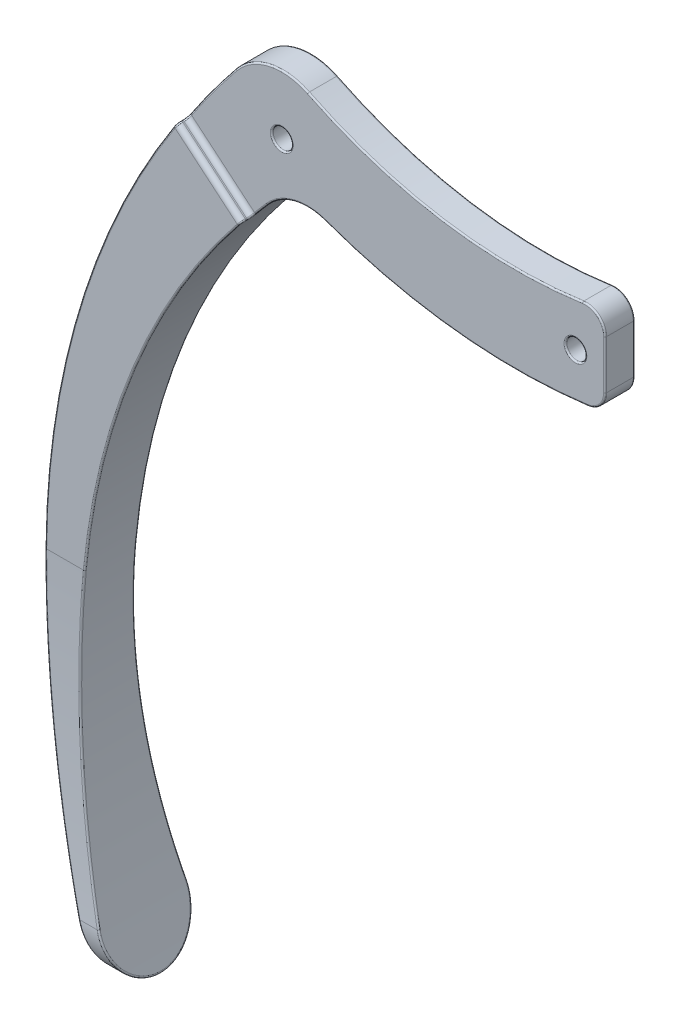
SolidWorks part; units mm, degrees
ref_plane "Front Plane" through (0, 0, 0) normal (0, 0, 1) x (1, 0, 0)
ref_plane "Top Plane" through (0, 0, 0) normal (0, 1, 0) x (1, 0, 0)
ref_plane "Right Plane" through (0, 0, 0) normal (1, 0, 0) x (0, 0, -1)
sketch "Sketch1" plane through (0, 0, 0) normal (0, 0, 1) x (1, 0, 0)
  line L0 (0, 4.5) -> (0, -4.5)
  line L1 (-46.08, -77.96) -> (-47.88, -77.96)
  arc A0 (0, 4.5) -> (-30, 8.5409) centre (-9.0055, 51.0244) cw
  arc A1 (0, -4.5) -> (-28.25, -1.8311) centre (-9.0055, 51.0244) cw
  arc A2 (-28.25, -1.8311) -> (-34.1009, -3.3287) centre (-30.0804, -6.8583) ccw
  arc A3 (-34.1009, -3.3287) -> (-46.08, -77.96) centre (19.2554, -50.17) ccw
  arc A4 (-30, 8.5409) -> (-37.3077, 6.9543) centre (-32.6582, 3.1619) ccw
  arc A5 (-37.3077, 6.9543) -> (-47.88, -77.96) centre (25.0724, -43.9277) ccw
  circle A6 centre (-32.6582, 3.1619) radius 1
  arc A7 (0, 0) -> (-28.6843, 3.0939) centre (-9.0055, 51.0244) cw construction
  circle A8 centre (-3, -0.4394) radius 1
  point P3 (0, 0)
  dimension "D2" = 47.388
  dimension "D3" = 56.25
  dimension "D4" = 28.25
  dimension "D6" = 5.35
  dimension "D7" = 71
  dimension "D9" = 6
  dimension "D10" = 80.5
  dimension "D13" = 2
  dimension "D1" = 9
  dimension "D5" = 30
  dimension "D8" = 77.96
  dimension "D11" = 47.88
  dimension "D12" = 1.8
  dimension "D14" = 3
sketch "Sketch2" plane through (0, 0, 0) normal (0, 0, 1) x (1, 0, 0)
  line L0 (0, -4.5) -> (0, -35) construction
  line L1 (-35.6168, -5.114) -> (-42.1466, 0.3652)
  line L2 (0, -4.5) -> (0, 4.5)
  line L3 (-47.88, -77.96) -> (-46.08, -77.96)
  line L5 (-47.88, -77.96) -> (-46.08, -77.96)
  line L6 (-35.6168, -5.114) -> (0, -35) construction
  arc A6 (-28.25, -1.8311) -> (0, -4.5) centre (-9.0055, 51.0244) ccw
  arc A7 (-28.25, -1.8311) -> (-34.1009, -3.3287) centre (-30.0804, -6.8583) ccw
  arc A8 (-34.1009, -3.3287) -> (-46.08, -77.96) centre (19.2554, -50.17) ccw
  arc A9 (-37.3077, 6.9543) -> (-47.88, -77.96) centre (25.0724, -43.9277) ccw
  arc A10 (-30, 8.5409) -> (-37.3077, 6.9543) centre (-32.6582, 3.1619) ccw
  arc A11 (-30, 8.5409) -> (0, 4.5) centre (-9.0055, 51.0244) ccw
  arc A14 (-35.6168, -5.114) -> (-46.08, -77.96) centre (19.2554, -50.17) ccw
  arc A15 (-42.1466, 0.3652) -> (-47.88, -77.96) centre (25.0724, -43.9277) ccw
  dimension "D5" = 50
  dimension "D1" = 0
extrude "Boss-Extrude1" add sketch "Sketch2" along normal mid plane 10
sketch "Sketch3" plane through (0, 0, 0) normal (1, 0, 0) x (0, 0, -1)
  line L0 (-2.625, -43.4348) -> (-2.625, 5.0652)
  line L1 (-2.625, 5.0652) -> (2.625, 5.0652) construction
  line L2 (2.625, 5.0652) -> (2.625, -43.4348)
  line L3 (-5, 0.3652) -> (5, 0.3652) construction
  line L4 (-2.625, 5.0652) -> (-26.7308, 5.0652)
  line L5 (-26.7308, 5.0652) -> (-26.7308, -87.6392)
  line L6 (-26.7308, -87.6392) -> (29.1462, -87.6392)
  line L7 (29.1462, -87.6392) -> (29.1462, 5.0652)
  line L8 (29.1462, 5.0652) -> (2.625, 5.0652)
  arc A0 (2.625, -43.4348) -> (4.4638, -72.3651) centre (231.1292, -43.4348) ccw
  arc A1 (4.4638, -72.3651) -> (-4.4638, -72.3651) centre (0, -72.9348) cw
  arc A2 (-4.4638, -72.3651) -> (-2.625, -43.4348) centre (-231.1292, -43.4348) ccw
  dimension "D2" = 4.5
  dimension "D1" = 5.25
  dimension "D3" = 78
  dimension "D4" = 29.5
  dimension "D5" = 4.7
extrude "Cut-Extrude1" cut sketch "Sketch3" against normal through all
sketch "Sketch4" plane through (0, 0, 0) normal (0, 0, 1) x (1, 0, 0)
  line L0 (-42.1466, 0.3652) -> (-35.6168, -5.114)
  line L2 (0, -4.5) -> (0, 4.5)
  line L3 (-47.88, -77.96) -> (-46.08, -77.96)
  line L4 (0, -4.5) -> (0, 4.5)
  circle A1 centre (-3, -0.4394) radius 1
  circle A2 centre (-3, -0.4394) radius 1
  circle A3 centre (-32.6582, 3.1619) radius 1
  circle A4 centre (-32.6582, 3.1619) radius 1
  arc A6 (-28.25, -1.8311) -> (0, -4.5) centre (-9.0055, 51.0244) ccw
  arc A7 (-28.25, -1.8311) -> (-34.1009, -3.3287) centre (-30.0804, -6.8583) ccw
  arc A8 (-34.1009, -3.3287) -> (-46.08, -77.96) centre (19.2554, -50.17) ccw
  arc A9 (-37.3077, 6.9543) -> (-47.88, -77.96) centre (25.0724, -43.9277) ccw
  arc A10 (-30, 8.5409) -> (-37.3077, 6.9543) centre (-32.6582, 3.1619) ccw
  arc A11 (-30, 8.5409) -> (0, 4.5) centre (-9.0055, 51.0244) ccw
  arc A12 (-28.25, -1.8311) -> (0, -4.5) centre (-9.0055, 51.0244) ccw
  arc A13 (-28.25, -1.8311) -> (-34.1009, -3.3287) centre (-30.0804, -6.8583) ccw
  arc A14 (-34.1009, -3.3287) -> (-35.6168, -5.114) centre (19.2554, -50.17) ccw
  arc A15 (-37.3077, 6.9543) -> (-42.1466, 0.3652) centre (25.0724, -43.9277) ccw
  arc A16 (-30, 8.5409) -> (-37.3077, 6.9543) centre (-32.6582, 3.1619) ccw
  arc A17 (-30, 8.5409) -> (0, 4.5) centre (-9.0055, 51.0244) ccw
  dimension "D1" = 0
  dimension "D2" = 0
  dimension "D3" = 0
extrude "Boss-Extrude3" add sketch "Sketch4" along normal mid plane 3
fillet "Fillet1" radius 2 2 edges at (0, -4.5, 0) (0, 4.5, 0)
fillet "Fillet2" radius 0.5 4 edges at (-38.8817, -2.3744, -1.5) (-38.8817, -2.3744, -2.625) (-38.8817, -2.3744, 2.625) (-38.8817, -2.3744, 1.5)
fillet "Fillet4" radius 0.15 42 edges at (-35.4975, -4.9691, 1.6096) (-35.6168, -5.114, 2.0625) (-35.6862, -5.1987, 2.4373) (-46.4745, -23.3264, 2.625) (-49.8772, -66.3465, 3.7766) (-46.3038, -77.4279, -0.2498) (-51.7431, -49.7154, -2.7113) (-46.4745, -23.3264, -2.625) (-35.7357, -5.2592, -2.5154) (-35.6168, -5.114, -2.0625) (-35.5472, -5.0294, -1.6877) (-34.704, -4.0248, -1.5) (-31.407, -1.6754, -1.5) (-15.1716, -4.8866, -1.5) (-0.4972, -4.0911, -1.5) (0, -0.3178, -1.5) (-0.6899, 3.647, -1.5) (-16.477, 4.2292, -1.5) (-33.9312, 9.0252, -1.5) (-39.6616, 3.9237, -1.5) (-42.0433, 0.5215, -1.6108) (-42.1466, 0.3652, -2.0625) (-42.2065, 0.2741, -2.4358) (-52.0374, -20.8122, -2.625) (-48.128, -77.4232, 0.3233) (-52.0374, -20.8122, 2.625) (-42.2494, 0.2087, 2.5141) (-42.1466, 0.3652, 2.0625) (-42.0865, 0.4562, 1.6892) (-31.6582, 3.1619, 1.5) (-33.9312, 9.0252, 1.5) (-16.477, 4.2292, 1.5) (-0.6899, 3.647, 1.5) (0, -0.3178, 1.5) (-0.4972, -4.0911, 1.5) (-15.1716, -4.8866, 1.5) (-31.407, -1.6754, 1.5) (-34.704, -4.0248, 1.5) (-39.6616, 3.9237, 1.5) (-2, -0.4394, 1.5)
